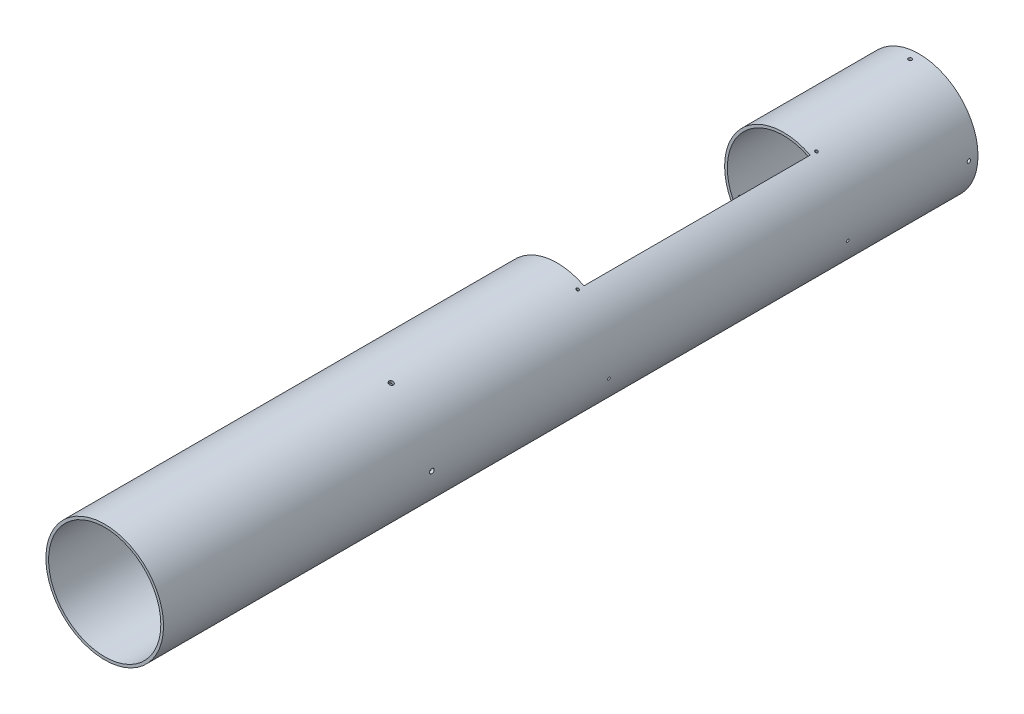
SolidWorks part; units mm, degrees
material "Hexcel AS4C (3000 Filaments)"
ref_plane "Front Plane" through (0, 0, 0) normal (0, 0, 1) x (1, 0, 0)
ref_plane "Top Plane" through (0, 0, 0) normal (0, 1, 0) x (1, 0, 0)
ref_plane "Right Plane" through (0, 0, 0) normal (1, 0, 0) x (0, 0, -1)
sketch "Sketch1" plane through (0, 0, 0) normal (0, 0, 1) x (1, 0, 0)
  circle A0 centre (0, 0) radius 62
  circle A1 centre (0, 0) radius 65
  dimension "D1" = 124
  dimension "D2" = 3
extrude "Boss-Extrude1" add sketch "Sketch1" along normal blind 900
sketch "Sketch2" plane through (0, 0, 0) normal (0, 1, 0) x (1, 0, 0)
  line L0 (62, 0) -> (-62, 0) construction
  circle A0 centre (0, -224) radius 1
  circle A1 centre (0, -264) radius 1
  dimension "D1" = 2
  dimension "D3" = 2
  dimension "D2" = 224
  dimension "D4" = 40
ref_plane "Plane1" through (0, 0, 0) normal (-0.7071, 0.7071, 0) x (0.7071, 0.7071, 0)
ref_plane "Plane2" through (-14.1421, 14.1421, 0) normal (-0.7071, 0.7071, 0) x (0.7071, 0.7071, 0)
sketch "Sketch4" plane through (-14.1421, 14.1421, 0) normal (-0.7071, 0.7071, 0) x (0.7071, 0.7071, 0)
  line L0 (-65, 0) -> (-65, -900) construction
  line L1 (-65, -150) -> (65, -150)
  line L2 (-65, -150) -> (-65, -400)
  line L3 (-65, -400) -> (65, -400)
  line L4 (65, -150) -> (65, -400)
  line L5 (65, -900) -> (65, 0) construction
  line L6 (65, 0) -> (-65, 0) construction
  dimension "D1" = 150
  dimension "D2" = 250
extrude "Cut-Extrude4" cut sketch "Sketch4" along normal blind 516
sketch "Sketch5" plane through (0, 0, 0) normal (0, 1, 0) x (1, 0, 0)
  line L0 (-62, 0) -> (62, 0) construction
  circle A0 centre (0, -10) radius 2
  dimension "D1" = 4
  dimension "D2" = 10
extrude "Cut-Extrude5" cut sketch "Sketch5" against normal blind 85
pattern_circular "CirPattern1" count 4 every 90 about axis through (0, 0, 900) along (0, 0, -1) of "Cut-Extrude5"
sketch "Sketch7" plane through (-14.1421, 14.1421, 0) normal (-0.7071, 0.7071, 0) x (0.7071, 0.7071, 0)
  line L0 (-61.8466, -150) -> (61.8466, -150) construction
  line L1 (58.6856, -400) -> (-58.6856, -400) construction
  circle A0 centre (0, -143) radius 1.5
  circle A1 centre (0, -407) radius 1.5
  dimension "D1" = 3
  dimension "D3" = 3
  dimension "D2" = 7
  dimension "D4" = 7
extrude "Cut-Extrude6" cut sketch "Sketch7" along normal blind 243
pattern_circular "CirPattern2" count 5 every 72 about axis through (0, 0, 900) along (0, 0, -1) of "Cut-Extrude6"
sketch "Sketch8" plane through (0, 0, 0) normal (1, 0, 0) x (0, 0, -1)
  line L0 (-900, 65) -> (-900, -65) construction
  circle A0 centre (-603.5, 0) radius 2.5
  dimension "D2" = 5
  dimension "D1" = 296.5
extrude "Cut-Extrude7" cut sketch "Sketch8" along normal blind 209
pattern_circular "CirPattern3" count 5 every 72 about axis through (0, 0, 900) along (0, 0, -1) of "Cut-Extrude7"
